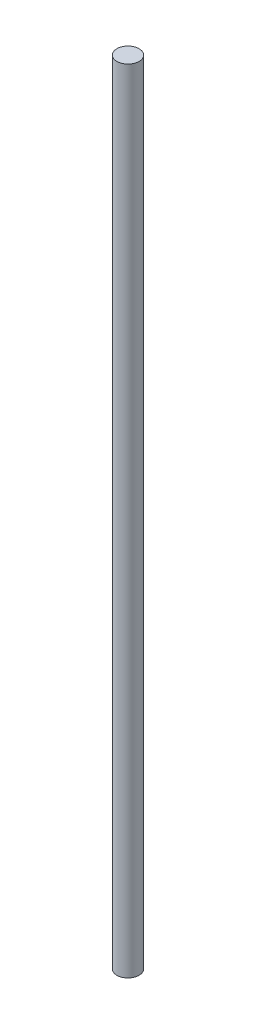
SolidWorks part; units mm, degrees
ref_plane "Alzado" through (0, 0, 0) normal (0, 0, 1) x (1, 0, 0)
ref_plane "Planta" through (0, 0, 0) normal (0, 1, 0) x (1, 0, 0)
ref_plane "Vista lateral" through (0, 0, 0) normal (1, 0, 0) x (0, 0, -1)
sketch "Croquis1" plane through (0, 0, 0) normal (0, 1, 0) x (1, 0, 0)
  circle A0 centre (0, 0) radius 3.5
  dimension "D1" = 7
extrude "Saliente-Extruir1" add sketch "Croquis1" along normal blind 250
sketch "Croquis2" plane through (0, 0, 0) normal (1, 0, 0) x (0, 0, -1)
  line L0 (3.5, 250) -> (-3.5, 250) construction
  line L1 (3.5, 250) -> (-3.5, 250) construction
  circle A0 centre (0, 250) radius 3.5
  dimension "D1" = 7
